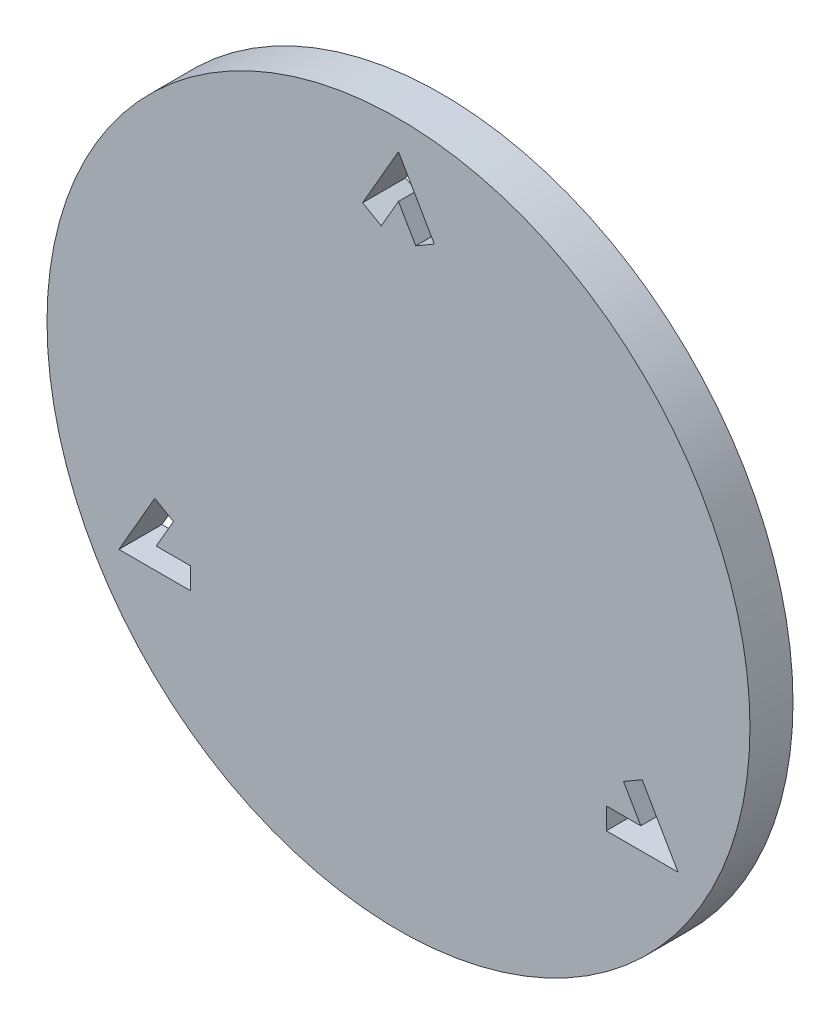
SolidWorks part; units mm, degrees
material "Acrílico (Impacto medio-alto)"
ref_plane "Alzado" through (0, 0, 0) normal (0, 0, 1) x (1, 0, 0)
ref_plane "Planta" through (0, 0, 0) normal (0, 1, 0) x (1, 0, 0)
ref_plane "Vista lateral" through (0, 0, 0) normal (1, 0, 0) x (0, 0, -1)
sketch "Croquis1" plane through (0, 0, 0) normal (0, 0, 1) x (1, 0, 0)
  line L0 (0, 45) -> (-5, 36.3397)
  line L1 (0, 45) -> (-38.9711, -22.5)
  line L2 (-38.9711, -22.5) -> (38.9711, -22.5)
  line L3 (38.9711, -22.5) -> (0, 45)
  line L4 (0, 45) -> (5, 36.3397)
  line L5 (5, 36.3397) -> (2.4019, 34.8397)
  line L6 (-5, 36.3397) -> (-2.4019, 34.8397)
  line L7 (-2.4019, 34.8397) -> (0, 39)
  line L8 (2.4019, 34.8397) -> (0, 39)
  line L9 (0, 39) -> (0, 45)
  line L10 (-38.9711, -22.5) -> (-28.9711, -22.5)
  line L11 (-28.9711, -22.5) -> (-28.9711, -19.5)
  line L12 (-38.9711, -22.5) -> (-33.9711, -13.8397)
  line L13 (-33.9711, -13.8397) -> (-31.3731, -15.3397)
  line L14 (-31.3731, -15.3397) -> (-33.775, -19.5)
  line L15 (-28.9711, -19.5) -> (-33.775, -19.5)
  line L16 (38.9711, -22.5) -> (33.9711, -13.8397)
  line L17 (33.9711, -13.8397) -> (31.3731, -15.3397)
  line L18 (38.9711, -22.5) -> (28.9711, -22.5)
  line L19 (28.9711, -22.5) -> (28.9711, -19.5)
  line L20 (31.3731, -15.3397) -> (33.775, -19.5)
  line L21 (28.9711, -19.5) -> (33.775, -19.5)
  circle A0 centre (0, 0) radius 49
  circle A1 centre (0, 0) radius 22.5 construction
  dimension "D1" = 98
  dimension "D2" = 45
  dimension "D3" = 10
  dimension "D4" = 3
  dimension "D5" = 3
  dimension "D6" = 10
  dimension "D7" = 10
  dimension "D8" = 3
  dimension "D9" = 3
  dimension "D10" = 10
  dimension "D11" = 10
  dimension "D12" = 3
  dimension "D13" = 3
extrude "Saliente-Extruir1" add sketch "Croquis1" along normal blind 6 contours A0 L3 L2 L1 L0 | L19 L21 L20 L17 L3 L5 L8 L7 L6 L1 L13 L14 L15 L11 L2
